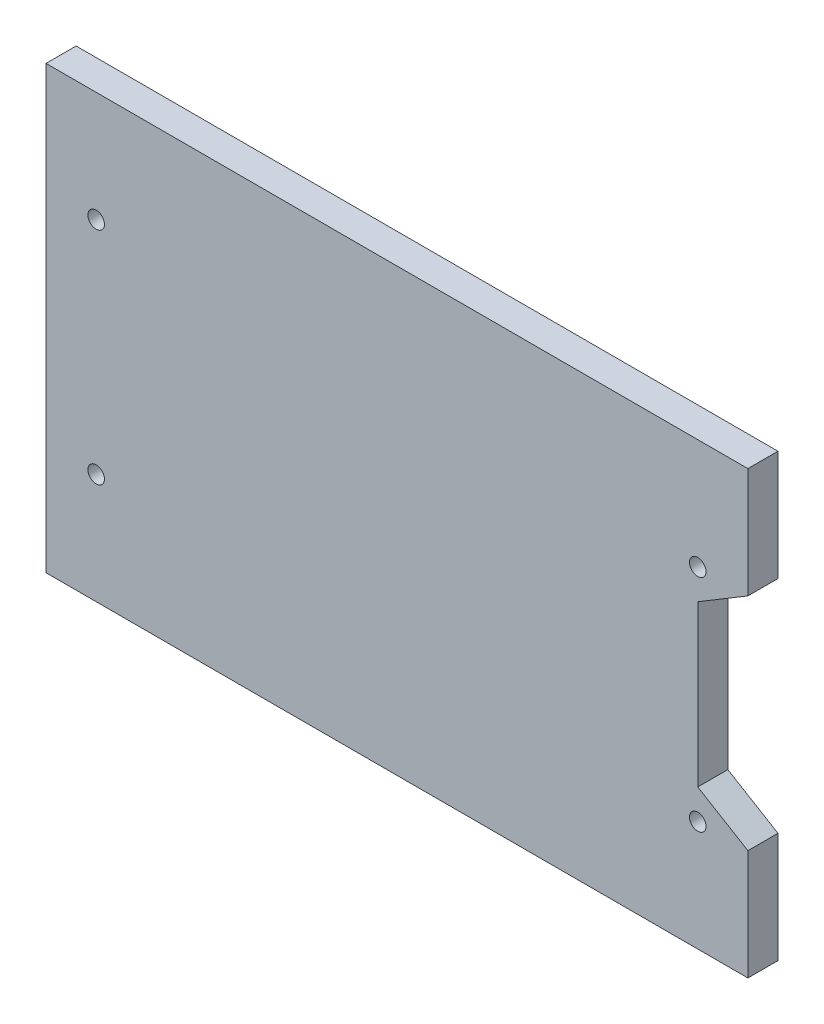
SolidWorks part; units mm, degrees
ref_plane "Front Plane" through (0, 0, 0) normal (0, 0, 1) x (1, 0, 0)
ref_plane "Top Plane" through (0, 0, 0) normal (0, 1, 0) x (1, 0, 0)
ref_plane "Right Plane" through (0, 0, 0) normal (1, 0, 0) x (0, 0, -1)
sketch "Sketch1" plane through (0, 0, 0) normal (0, 0, 1) x (1, 0, 0)
  line L0 (0, 0) -> (140, 0)
  line L1 (140, 88) -> (140, 66)
  line L2 (0, 88) -> (0, 0)
  line L3 (130, 60) -> (140, 66)
  line L4 (0, 88) -> (140, 88)
  line L5 (130, 60) -> (130, 28)
  line L6 (130, 28) -> (140, 22)
  line L7 (140, 0) -> (140, 22)
  line L8 (10, 22) -> (130, 22) construction
  line L9 (130, 44) -> (0, 44) construction
  circle A0 centre (10, 22) radius 1.65
  circle A1 centre (130, 66) radius 1.65
  circle A2 centre (130, 22) radius 1.65
  circle A3 centre (10, 66) radius 1.65
  dimension "D4" = 10
  dimension "D9" = 3.3
  dimension "D1" = 88
  dimension "D2" = 140
  dimension "D3" = 22
  dimension "D5" = 120
  dimension "D6" = 22
  dimension "D7" = 130
  dimension "D8" = 32
extrude "Boss-Extrude1" add sketch "Sketch1" along normal blind 6
